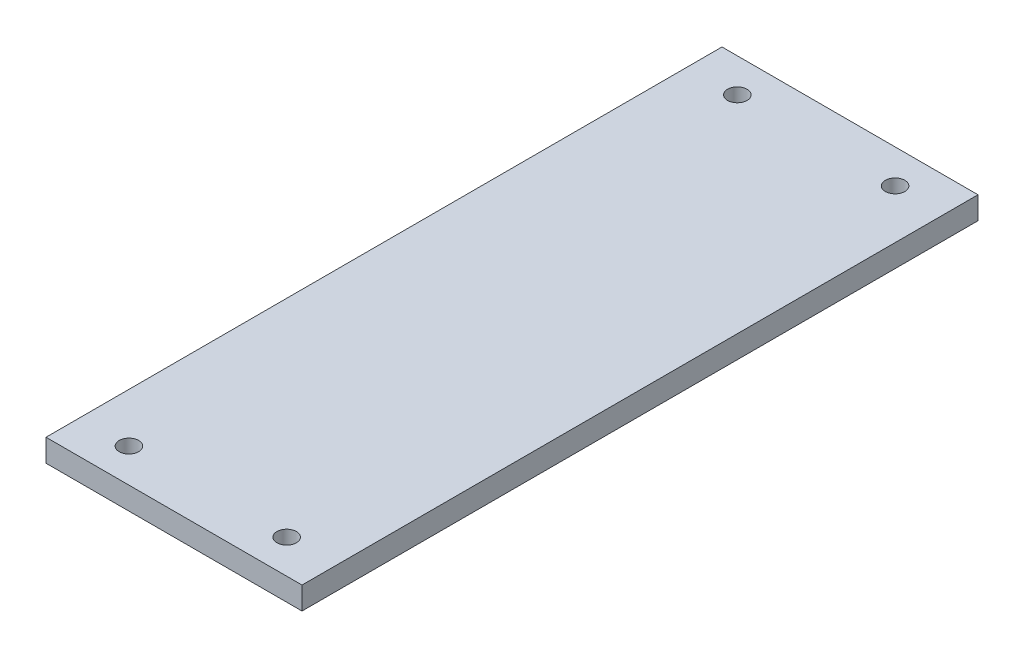
SolidWorks part; units mm, degrees
ref_plane "Front Plane" through (0, 0, 0) normal (0, 0, 1) x (1, 0, 0)
ref_plane "Top Plane" through (0, 0, 0) normal (0, 1, 0) x (1, 0, 0)
ref_plane "Right Plane" through (0, 0, 0) normal (1, 0, 0) x (0, 0, -1)
sketch "Sketch2" plane through (0, 0, 0) normal (0, 1, 0) x (1, 0, 0)
  line L1 (-36.0719, -95.25) -> (36.0719, -95.25)
  line L2 (-36.0719, -95.25) -> (-36.0719, 95.25)
  line L3 (-36.0719, 95.25) -> (36.0719, 95.25)
  line L4 (36.0719, -95.25) -> (36.0719, 95.25)
  line L5 (-36.0719, -95.25) -> (36.0719, 95.25) construction
  line L6 (-36.0719, 95.25) -> (36.0719, -95.25) construction
  point P0 (0, 0)
  dimension "D1" = 190.5
  dimension "D2" = 72.1437
extrude "Boss-Extrude1" add sketch "Sketch2" along normal blind 6.35
sketch "Sketch3" plane through (0, 6.35, 0) normal (0, 1, 0) x (1, 0, 0)
  line L0 (0, -95.25) -> (0, 95.25) construction
  line L1 (-36.0719, -95.25) -> (36.0719, -95.25) construction
  line L2 (36.0719, 95.25) -> (-36.0719, 95.25) construction
  line L8 (-36.0719, 85.725) -> (36.0719, 85.725) construction
  line L10 (-36.0719, 95.25) -> (-36.0719, -95.25) construction
  line L11 (36.0719, -95.25) -> (36.0719, 95.25) construction
  line L12 (-3.4925, 0) -> (3.4925, 0) construction
  circle A4 centre (-22.225, 85.725) radius 2.75
  circle A5 centre (22.225, 85.725) radius 2.75
  circle A6 centre (22.225, -85.725) radius 2.75
  circle A7 centre (-22.225, -85.725) radius 2.75
  point P6 (0, 57.5747)
  dimension "D3" = 5.5
  dimension "D1" = 9.525
  dimension "D2" = 44.45
extrude "Cut-Extrude1" cut sketch "Sketch3" against normal blind 6.35
